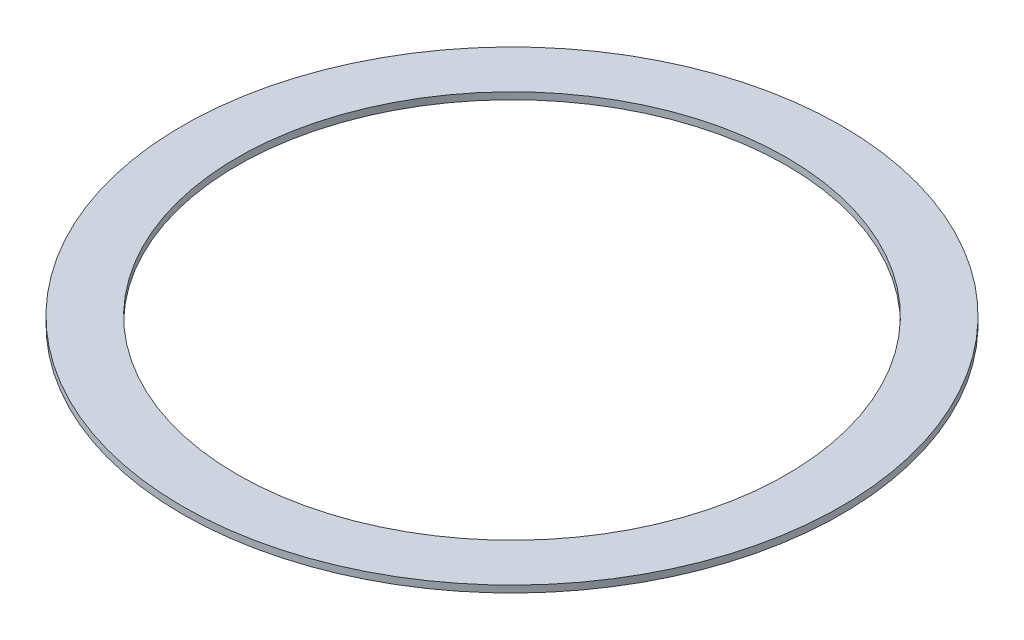
SolidWorks part; units mm, degrees
material "POM Acetal Copolymer"
ref_plane "Front Plane" through (0, 0, 0) normal (0, 0, 1) x (1, 0, 0)
ref_plane "Top Plane" through (0, 0, 0) normal (0, 1, 0) x (1, 0, 0)
ref_plane "Right Plane" through (0, 0, 0) normal (1, 0, 0) x (0, 0, -1)
sketch "Sketch1" plane through (0, 0, 0) normal (0, 1, 0) x (1, 0, 0)
  circle A0 centre (0, 0) radius 80
  circle A1 centre (0, 0) radius 96
  dimension "D1" = 160
  dimension "D2" = 192
extrude "Boss-Extrude1" add sketch "Sketch1" along normal blind 2
